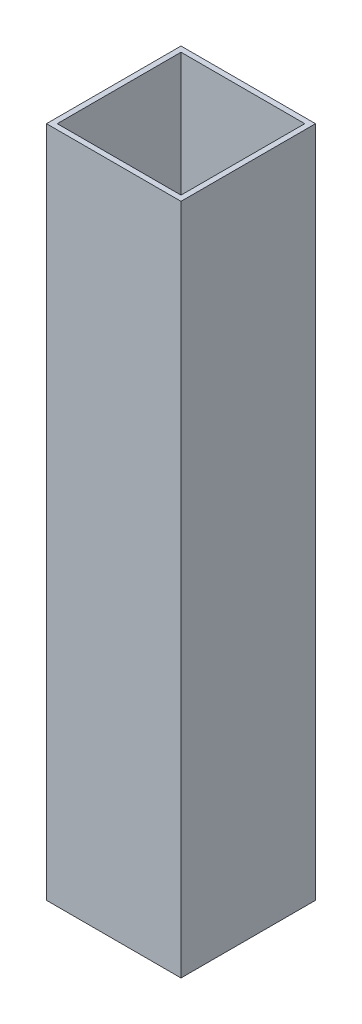
SolidWorks part; units mm, degrees
material "ASTM A36 Steel"
ref_plane "Front Plane" through (0, 0, 0) normal (0, 0, 1) x (1, 0, 0)
ref_plane "Top Plane" through (0, 0, 0) normal (0, 1, 0) x (1, 0, 0)
ref_plane "Right Plane" through (0, 0, 0) normal (1, 0, 0) x (0, 0, -1)
sketch "Sketch1" plane through (0, 0, 0) normal (0, 0, 1) x (1, 0, 0)
  line L0 (0, 0) -> (0, 250)
  dimension "D1" = 250
other "Ptr ASTM A36 50X50X2(1)"
ref_plane "Plane1" through (0, 0, 0) normal (0, 1, 0) x (-1, 0, 0)
sketch "Sketch21" plane through (0, 0, 0) normal (0, 1, 0) x (-1, 0, 0)
  line L1 (25, 25) -> (-25, 25)
  line L2 (25, 25) -> (25, -25)
  line L3 (25, -25) -> (-25, -25)
  line L4 (-25, 25) -> (-25, -25)
  line L5 (25, 25) -> (-25, -25) construction
  line L6 (25, -25) -> (-25, 25) construction
  line L7 (23, 23) -> (-23, 23)
  line L8 (23, 23) -> (23, -23)
  line L9 (23, -23) -> (-23, -23)
  line L10 (-23, 23) -> (-23, -23)
  line L11 (23, 23) -> (-23, -23) construction
  line L12 (23, -23) -> (-23, 23) construction
  point P0 (0, 0)
  point P6 (0, 0)
  point P11 (0, 0)
  dimension "D1" = 50
  dimension "D2" = 2
equation "\"largo viga enterrada\"=0.25"
equation "\"D1@Sketch1\"=\"largo viga enterrada\""
